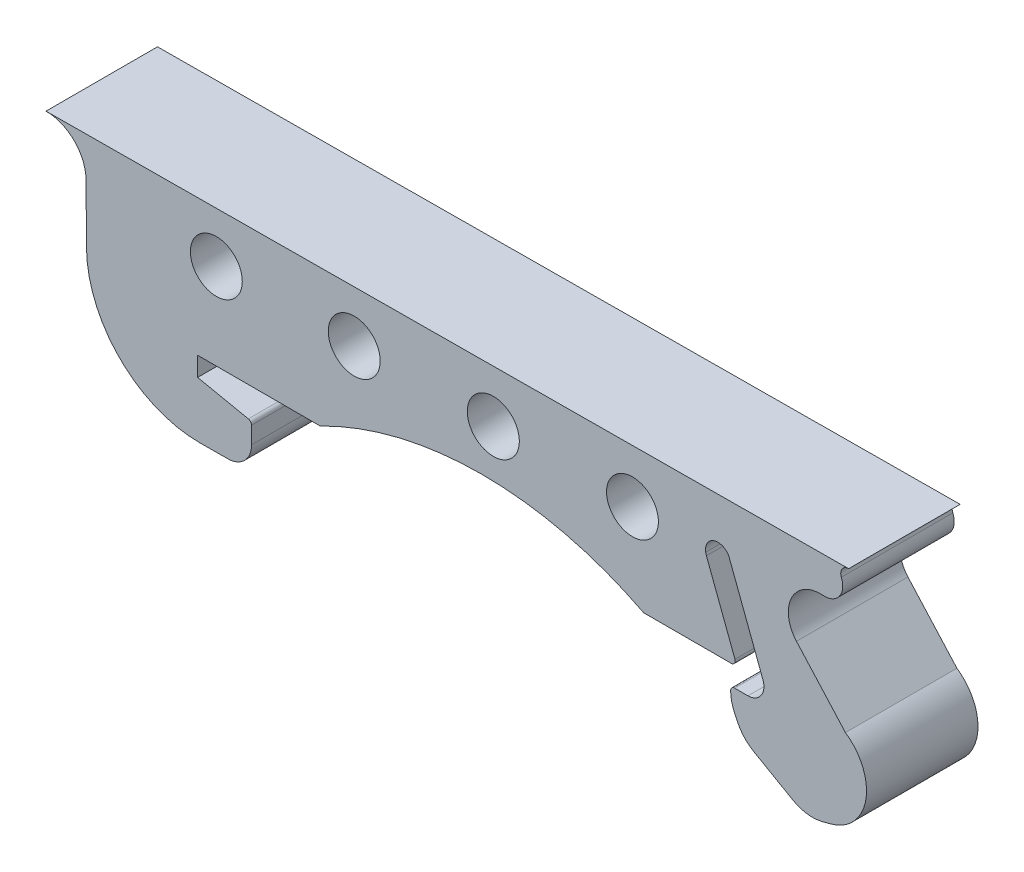
SolidWorks part; units mm, degrees
ref_plane "Front" through (0, 0, 0) normal (0, 0, 1) x (1, 0, 0)
ref_plane "Top" through (0, 0, 0) normal (0, 1, 0) x (1, 0, 0)
ref_plane "Right" through (0, 0, 0) normal (1, 0, 0) x (0, 0, -1)
sketch "Szkic1" plane through (0, 0, 0) normal (0, 0, 1) x (-1, 0, 0)
  line L0 (-42.2065, -1.1434) -> (-42.1873, -4.171)
  line L1 (-42.1873, -4.171) -> (54.6938, -3.5571)
  line L2 (54.6938, -3.5571) -> (54.6746, -0.5295)
  line L3 (54.6746, -0.5295) -> (31.895, -0.6739)
  line L4 (29.3793, 1.8076) -> (29.3519, 5.5157)
  line L5 (22.2408, 12.5348) -> (20.4729, 12.5236)
  line L6 (-18.5118, -0.9933) -> (-42.2065, -1.1434)
  line L7 (-16.708, 1.2588) -> (-16.932, 1.257)
  line L8 (21.1985, 2.4245) -> (-4.9371, 2.4274) construction
  line L9 (12.5385, 2.4254) -> (12.5385, -1.991) construction
  line L10 (14.6779, 7.8414) -> (22.3731, 7.8414)
  line L11 (22.3731, 7.8414) -> (22.3731, 9.0475)
  line L12 (22.3731, 9.0475) -> (19.1884, 9.708)
  line L13 (3.8029, 2.4225) -> (3.8029, -1.991) construction
  line L14 (-4.9371, 2.4274) -> (-4.9371, -1.8351) construction
  line L15 (18.9892, 9.9512) -> (18.9824, 11.0141)
  line L16 (-5.6423, 7.8414) -> (-11.1386, 7.8414)
  line L17 (21.1985, 2.4254) -> (21.1985, -11.6582) construction
  line L18 (-19.6358, 10.5269) -> (-19.6358, 20.4985) construction
  line L19 (-11.3724, 7.5028) -> (-9.5806, 2.7717)
  line L20 (-9.5806, 2.7717) -> (-9.5366, 2.5946)
  line L21 (-11.1012, 9.3411) -> (-11.1012, 9.3328)
  line L22 (-10.9907, 2.0931) -> (-11.0623, 2.2821)
  line L24 (-11.0623, 2.2821) -> (-13.1251, 7.7286)
  line L25 (-12.1899, 9.0828) -> (-11.3512, 9.0828)
  line L26 (-11.3281, 10.3819) -> (-11.5214, 10.8039)
  line L27 (-12.5515, 11.9322) -> (-15.0023, 13.3367)
  line L29 (-15.2353, 4.5943) -> (-18.3121, 8.0243)
  line L30 (-16.8796, 13.5858) -> (-17.3764, 13.4554)
  arc A0 (29.3519, 5.5157) -> (22.2408, 12.5348) centre (22.2408, 5.4232) ccw
  arc A1 (-10.9907, 2.0931) -> (-9.5366, 2.5946) centre (-10.3005, 2.4506) ccw
  arc A2 (-5.6423, 7.8414) -> (14.6779, 7.8414) centre (4.5178, 27.6733) ccw
  arc A3 (-18.3121, 8.0243) -> (-17.3764, 13.4554) centre (-16.6082, 10.5269) cw
  arc A4 (-16.708, 1.2588) -> (-15.2353, 4.5943) centre (-16.724, 3.2588) ccw
  arc A5 (-18.0541, -0.2994) -> (-16.932, 1.257) centre (-17.018, 0.1363) cw
  circle A6 centre (21.1985, 2.4254) radius 1.63
  circle A7 centre (-4.9371, 2.4274) radius 1.6279
  circle A8 centre (3.8029, 2.4225) radius 1.6342
  arc A9 (31.895, -0.6739) -> (29.3793, 1.8076) centre (31.8792, 1.8261) cw
  circle A10 centre (12.5385, 2.4254) radius 1.6313
  arc A11 (-18.0541, -0.2994) -> (-18.5118, -0.9933) centre (-18.515, -0.4933) cw
  arc A12 (-13.1251, 7.7286) -> (-12.1899, 9.0828) centre (-12.1899, 8.0828) cw
  arc A13 (-15.0023, 13.3367) -> (-16.8796, 13.5858) centre (-16.2453, 11.1676) ccw
  arc A14 (-11.1012, 9.3411) -> (-11.3281, 10.3819) centre (-13.6012, 9.3411) ccw
  arc A15 (18.9824, 11.0141) -> (20.4729, 12.5236) centre (20.4824, 11.0236) cw
  arc A16 (19.1884, 9.708) -> (18.9892, 9.9512) centre (19.2392, 9.9528) cw
  arc A17 (-11.3724, 7.5028) -> (-11.1386, 7.8414) centre (-11.1386, 7.5914) cw
  arc A18 (-11.1012, 9.3328) -> (-11.3512, 9.0828) centre (-11.3512, 9.3328) cw
  arc A19 (-12.5515, 11.9322) -> (-11.5214, 10.8039) centre (-13.7944, 9.7631) cw
  dimension "D2" = 2.5
  dimension "D3" = 0.5
  dimension "D4" = 2
  dimension "D5" = 2.5
  dimension "D6" = 0.25
  dimension "D8" = 8.5346
  dimension "D9" = 2.5
  dimension "D11" = 1
  dimension "D1" = 8.66
  dimension "D7" = 30.0903
  dimension "D10" = 1.2414
extrude "Dodanie-wyciągnięcie1" add sketch "Szkic1" along normal blind 37.7
sketch "Szkic2" plane through (-0.0247, 3.9035, 0) normal (-0.0063, 1, 0) x (1, 0.0063, 0)
  line L0 (-54.6701, -37.7) -> (-54.6701, 0) construction
  line L1 (42.2129, -37.7) -> (-54.6701, -37.7)
  line L2 (42.2129, -37.7) -> (42.2129, -27.7)
  line L3 (42.2129, -27.7) -> (-54.6701, -27.7)
  line L4 (-54.6701, -37.7) -> (-54.6701, -27.7)
  dimension "D1" = 10
extrude "Wytnij-wyciągnięcie1" cut sketch "Szkic2" against normal up to surface (3.0276 mm away)
sketch "Szkic4" plane through (-54.669, -0.3464, 0) normal (-1, -0.0063, 0) x (0, 0, 1)
  line L1 (0, 3.9036) -> (27.7, 3.9036)
  line L2 (0, 3.9036) -> (0, 0.876)
  line L3 (0, 0.876) -> (27.7, 0.876)
  line L4 (27.7, 3.9036) -> (27.7, 0.876)
extrude "Dodanie-wyciągnięcie2" add sketch "Szkic4" along normal blind 4.6
sketch "Szkic5" plane through (42.212, 0.2675, 0) normal (1, 0.0063, 0) x (0, 0, -1)
  line L0 (-27.7, 0.876) -> (-27.7, 3.9036) construction
  line L1 (0, 3.9036) -> (-27.7, 3.9036)
  line L2 (0, 3.9036) -> (0, 0.876)
  line L3 (0, 0.876) -> (-27.7, 0.876)
  line L4 (-27.7, 3.9036) -> (-27.7, 0.876)
extrude "Dodanie-wyciągnięcie4" add sketch "Szkic5" along normal blind 4.6
sketch "Szkic6" plane through (-0.0247, 3.9035, 0) normal (-0.0063, 1, 0) x (1, 0.0063, 0)
  line L0 (-63.3099, -5) -> (53.8869, -5) construction
  line L1 (42.2129, 0) -> (-59.2701, 0) construction
  line L2 (-67.59, -10) -> (59.7453, -10) construction
  line L3 (-51.2701, -20.6894) -> (-51.2701, 8.3773) construction
  line L4 (-59.2701, -27.7) -> (-59.2701, 0) construction
  line L5 (38.8129, -22.6628) -> (38.8129, 14.7417) construction
  line L6 (46.8129, 0) -> (46.8129, -27.7) construction
  line L7 (43.8129, -22.6628) -> (43.8129, 10.2565) construction
  line L8 (-56.2701, -24.3215) -> (-56.2701, 7.5332) construction
  line L9 (-51.2701, -5) -> (-56.2701, -10) construction
  line L10 (43.8129, -5) -> (38.8129, -10) construction
  circle A0 centre (-53.7701, -7.5) radius 2.5
  circle A1 centre (41.3129, -7.5) radius 2.5
  dimension "D1" = 5
  dimension "D2" = 5
  dimension "D3" = 8
  dimension "D4" = 8
  dimension "D5" = 5
  dimension "D6" = 5
extrude "Wytnij-wyciągnięcie2" cut sketch "Szkic6" against normal up to surface (3.0276 mm away)
sketch "Szkic7" plane through (0, 0, 0) normal (0, 0, -1) x (-1, 0, 0)
  line L1 (-47.046, 4.9571) -> (62.9578, 4.9571)
  line L2 (-47.046, 4.9571) -> (-47.046, -54.7875)
  line L3 (-47.046, -54.7875) -> (62.9578, -54.7875)
  line L4 (62.9578, 4.9571) -> (62.9578, -54.7875)
extrude "Wytnij-wyciągnięcie4" cut sketch "Szkic7" against normal blind 30.7
ref_plane "Płaszczyzna1" through (-6.6861, -0.0424, 0) normal (1, 0.0063, 0) x (0, 0, -1)
